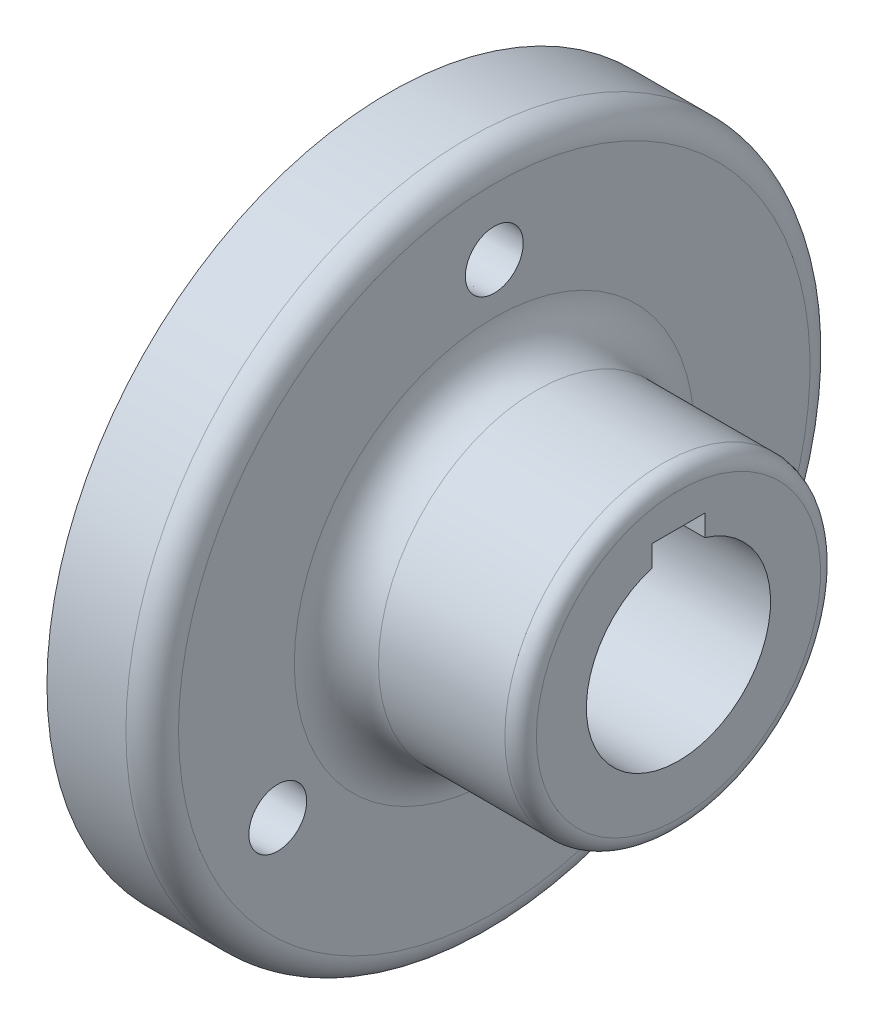
SolidWorks part; units mm, degrees
ref_plane "Front Plane" through (0, 0, 0) normal (0, 0, 1) x (1, 0, 0)
ref_plane "Top Plane" through (0, 0, 0) normal (0, 1, 0) x (1, 0, 0)
ref_plane "Right Plane" through (0, 0, 0) normal (1, 0, 0) x (0, 0, -1)
sketch "Sketch1" plane through (0, 0, 0) normal (0, 0, 1) x (1, 0, 0)
  line L0 (-55, 0) -> (0, 0)
  line L1 (0, 0) -> (0, 65)
  line L2 (0, 65) -> (-15, 65)
  line L3 (-20, 60) -> (-20, 38)
  line L4 (-28, 30) -> (-52, 30)
  line L5 (-55, 27) -> (-55, 0)
  arc A0 (-20, 38) -> (-28, 30) centre (-28, 38) cw
  arc A1 (-15, 65) -> (-20, 60) centre (-15, 60) ccw
  arc A2 (-52, 30) -> (-55, 27) centre (-52, 27) ccw
  point P11 (-20, 65)
  dimension "D4" = 8
  dimension "D5" = 5
  dimension "D6" = 3
  dimension "D1" = 20
  dimension "D2" = 65
  dimension "D3" = 55
  dimension "D7" = 30
revolve "Revolve1" add sketch "Sketch1" angle 360 about L0
sketch "Sketch2" plane through (-55, 0, 0) normal (-1, 0, 0) x (0, 0, 1)
  circle A0 centre (0, 0) radius 17.5
  dimension "D1" = 35
extrude "Cut-Extrude1" cut sketch "Sketch2" against normal through all
sketch "Sketch3" plane through (0, 0, 0) normal (1, 0, 0) x (0, 0, -1)
  line L1 (-5, 14.2) -> (5, 14.2)
  line L2 (-5, 14.2) -> (-5, 20.8)
  line L3 (-5, 20.8) -> (5, 20.8)
  line L4 (5, 14.2) -> (5, 20.8)
  line L5 (-5, 14.2) -> (5, 20.8) construction
  line L6 (-5, 20.8) -> (5, 14.2) construction
  circle A0 centre (0, 0) radius 17.5 construction
  point P0 (0, 17.5)
  dimension "D1" = 10
  dimension "D2" = 3.3
extrude "Cut-Extrude2" cut sketch "Sketch3" against normal through all
ref_plane "Plane2" through (0, -30, 0) normal (0, -1, 0) x (-1, 0, 0)
sketch "Sketch4" plane through (0, -30, 0) normal (0, -1, 0) x (-1, 0, 0)
  circle A0 centre (40.2298, 0) radius 4
  dimension "D1" = 8
extrude "Cut-Extrude3" cut sketch "Sketch4" against normal blind 10
cosmetic thread "Cosmetic Thread1" parameters "D2"=10
sketch "Sketch5" plane through (0, 0, 0) normal (1, 0, 0) x (0, 0, -1)
  line L0 (-1.65, -47.5) -> (1.65, -47.5) construction
  line L1 (-1.65, -39.5) -> (1.65, -39.5)
  line L2 (-1.65, -55.5) -> (1.65, -55.5)
  line L3 (-40.3112, 25.1789) -> (-41.9612, 22.3211) construction
  line L4 (-33.383, 21.1789) -> (-35.033, 18.3211)
  line L5 (-47.2394, 29.1789) -> (-48.8894, 26.3211)
  line L6 (41.9612, 22.3211) -> (40.3112, 25.1789) construction
  line L7 (35.033, 18.3211) -> (33.383, 21.1789)
  line L8 (48.8894, 26.3211) -> (47.2394, 29.1789)
  arc A0 (-1.65, -39.5) -> (-1.65, -55.5) centre (-1.65, -47.5) ccw
  arc A1 (1.65, -55.5) -> (1.65, -39.5) centre (1.65, -47.5) ccw
  circle A2 centre (0, 0) radius 47.5
  arc A3 (-33.383, 21.1789) -> (-47.2394, 29.1789) centre (-40.3112, 25.1789) ccw
  arc A4 (-48.8894, 26.3211) -> (-35.033, 18.3211) centre (-41.9612, 22.3211) ccw
  arc A5 (35.033, 18.3211) -> (48.8894, 26.3211) centre (41.9612, 22.3211) ccw
  arc A6 (47.2394, 29.1789) -> (33.383, 21.1789) centre (40.3112, 25.1789) ccw
  circle A7 centre (0, 47.5) radius 7
  circle A8 centre (41.1362, -23.75) radius 7
  circle A9 centre (-41.1362, -23.75) radius 7
  point P2 (0, -47.5)
  point P15 (-41.1362, 23.75)
  point P22 (41.1362, 23.75)
  point P27 (0, 0)
  point P33 (0, 0)
  dimension "D2" = 8
  dimension "D3" = 95
  dimension "D5" = 14
  dimension "D1" = 3.3
  dimension "D4" = 3
  dimension "D6" = 3
extrude "Cut-Extrude5" cut sketch "Sketch5" against normal through all draft 4.289 contours A2 A7 | A2 A7 | A2 A9 | A2 A9 | A2 A8 | A2 A8
mirror "Mirror1" about plane through (0, 0, 0) normal (-1, 0, 0) of bodies 107
sketch "Sketch6" plane through (0, 0, 0) normal (1, 0, 0) x (0, 0, -1)
  circle A0 centre (0, 0) radius 81.55
extrude "Cut-Extrude6" cut sketch "Sketch6" against normal blind 60
